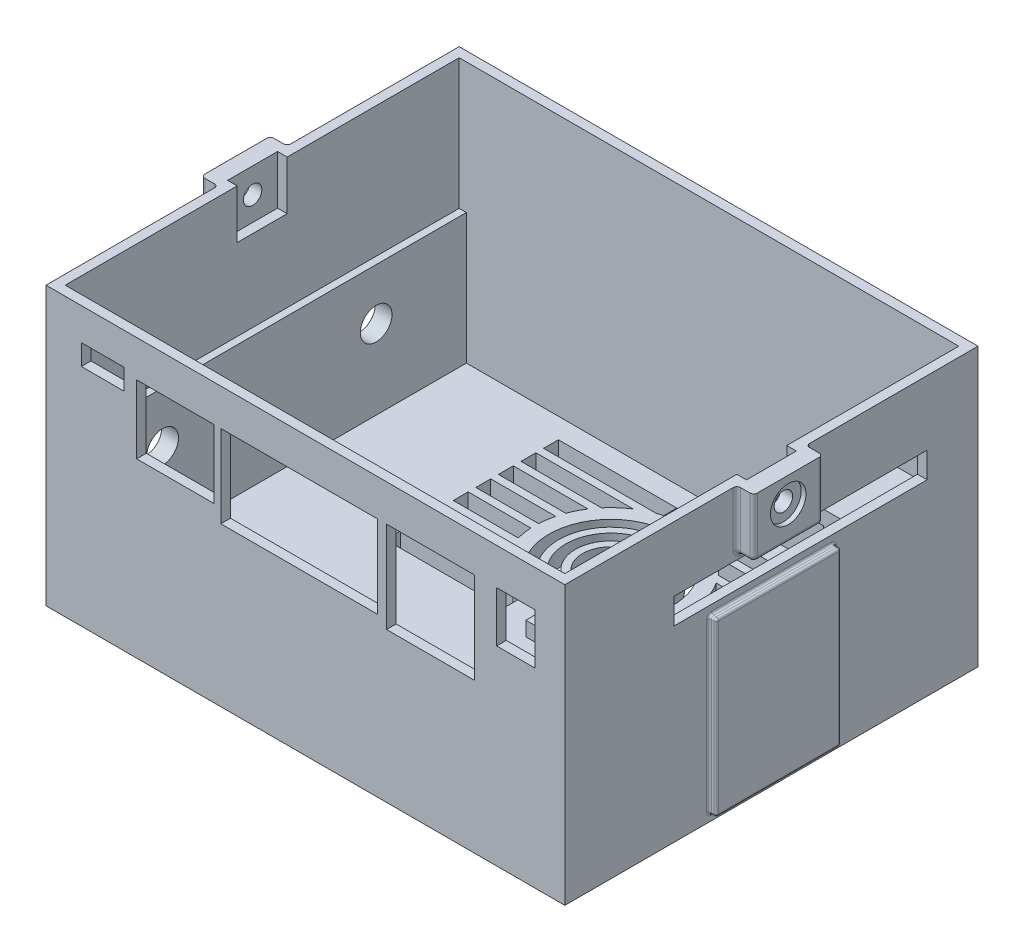
SolidWorks part; units mm, degrees
material "Custom Plastic"
ref_plane "Front Plane" through (0, 0, 0) normal (0, 0, 1) x (1, 0, 0)
ref_plane "Top Plane" through (0, 0, 0) normal (0, 1, 0) x (1, 0, 0)
ref_plane "Right Plane" through (0, 0, 0) normal (1, 0, 0) x (0, 0, -1)
sketch "Sketch1" plane through (0, 0, 0) normal (0, 1, 0) x (1, 0, 0)
  line L1 (54, -43) -> (-54, -43)
  line L2 (54, -43) -> (54, 43)
  line L3 (54, 43) -> (-54, 43)
  line L4 (-54, -43) -> (-54, 43)
  line L5 (54, -43) -> (-54, 43) construction
  line L6 (54, 43) -> (-54, -43) construction
  point P0 (0, 0)
  dimension "D1" = 108
  dimension "D2" = 86
extrude "Boss-Extrude1" add sketch "Sketch1" along normal blind 1.5
sketch "Sketch2" plane through (0, 1.5, 0) normal (0, 1, 0) x (1, 0, 0)
  line L4 (-54, 43) -> (-54, -43)
  line L5 (-54, -43) -> (54, -43)
  line L6 (54, -43) -> (54, 43)
  line L7 (54, 43) -> (-54, 43)
  line L8 (-54, 43) -> (-54, -43)
  line L9 (-54, -43) -> (54, -43)
  line L10 (54, -43) -> (54, 43)
  line L11 (54, 43) -> (-54, 43)
  dimension "D1" = 0
extrude "Boss-Extrude2" add sketch "Sketch2" along normal blind 56.3
shell "Shell1" thickness 2
sketch "Sketch3" plane through (54, 0, 0) normal (1, 0, 0) x (0, 0, -1)
  line L0 (0, -5.9802) -> (0, 60.3396) construction
  line L1 (-43, 57.8) -> (43, 57.8) construction
  line L2 (5.2, 47.5875) -> (-5.2, 47.5875)
  line L3 (5.2, 47.5875) -> (5.2, 57.8)
  line L4 (5.2, 57.8) -> (-5.2, 57.8)
  line L5 (-5.2, 47.5875) -> (-5.2, 57.8)
  line L6 (5.2, 47.5875) -> (-5.2, 57.8) construction
  line L7 (5.2, 57.8) -> (-5.2, 47.5875) construction
  point P3 (0, 52.6937)
  dimension "D1" = 10.2125
  dimension "D2" = 10.4
extrude "Cut-Extrude1" cut sketch "Sketch3" against normal through all
sketch "Sketch4" plane through (54, 0, 0) normal (1, 0, 0) x (0, 0, -1)
  line L0 (-7.2, 57.8) -> (-7.2, 45.5875)
  line L1 (-43, 57.8) -> (-5.2, 57.8) construction
  line L2 (-7.2, 45.5875) -> (7.2, 45.5875)
  line L3 (7.2, 45.5875) -> (7.2, 57.8)
  line L4 (5.2, 57.8) -> (43, 57.8) construction
  line L5 (7.2, 57.8) -> (-7.2, 57.8)
  line L6 (-5.2, 57.8) -> (-5.2, 47.5875) construction
  line L7 (5.2, 47.5875) -> (5.2, 57.8) construction
  line L8 (-5.2, 47.5875) -> (5.2, 47.5875) construction
  dimension "D1" = 2
  dimension "D2" = 2
  dimension "D3" = 2
extrude "Boss-Extrude3" add sketch "Sketch4" along normal blind 3.5
ref_plane "Plane1" through (0, 0, 0) normal (1, 0, 0) x (0, 0, -1)
mirror "Mirror1" about plane through (0, 0, 0) normal (1, 0, 0) of "Boss-Extrude3"
sketch "Sketch5" plane through (57.5, 0, 0) normal (1, 0, 0) x (0, 0, -1)
  line L0 (-7.2, 45.5875) -> (7.2, 45.5875) construction
  circle A0 centre (0, 52.5875) radius 1.925
  point P4 (0, 45.5875)
  dimension "D1" = 3.85
  dimension "D2" = 7
extrude "Cut-Extrude2" cut sketch "Sketch5" against normal through all
fillet "Fillet1" radius 0.75 1 edges at (57.5, 51.6937, 7.2)
fillet "Fillet2" radius 0.75 3 edges at (55.375, 45.5875, 7.2) (57.5, 45.5875, -0.375) (57.2803, 45.5875, 6.9803)
fillet "Fillet3" radius 0.75 3 edges at (55.375, 45.5875, -7.2) (57.5, 52.0687, -7.2) (57.2803, 45.8072, -7.2)
fillet "Fillet4" radius 0.75 5 edges at (54, 45.5875, 0) (54, 45.8072, 6.9803) (54, 52.0687, -7.2) (54, 45.8072, -6.9803) (54, 52.0687, 7.2)
fillet "Fillet5" radius 0.75 1 edges at (-57.5, 51.6937, -7.2)
fillet "Fillet6" radius 0.75 3 edges at (-55.375, 45.5875, -7.2) (-57.2803, 45.5875, -6.9803) (-57.5, 45.5875, 0.375)
fillet "Fillet7" radius 0.75 3 edges at (-55.375, 45.5875, 7.2) (-57.2803, 45.8072, 7.2) (-57.5, 52.0687, 7.2)
fillet "Fillet8" radius 0.75 5 edges at (-54, 52.0687, -7.2) (-54, 45.8072, -6.9803) (-54, 45.5875, 0) (-54, 45.8072, 6.9803) (-54, 52.0687, 7.2)
sketch "Sketch6" plane through (52, 0, 0) normal (-1, 0, 0) x (0, 0, 1)
  line L0 (-43, 0) -> (43, 0) construction
  line L1 (11, 35.26) -> (-11, 35.26)
  line L2 (11, 35.26) -> (11, 3.5)
  line L3 (11, 3.5) -> (-11, 3.5)
  line L4 (-11, 35.26) -> (-11, 3.5)
  line L5 (11, 35.26) -> (-11, 3.5) construction
  line L6 (11, 3.5) -> (-11, 35.26) construction
  line L7 (-43, 57.8) -> (-43, 0) construction
  point P0 (0, 19.38)
  point P7 (0, 3.5)
  dimension "D1" = 3.5
  dimension "D2" = 22
  dimension "D3" = 31.76
  dimension "D4" = 32
extrude "Cut-Extrude3" cut sketch "Sketch6" against normal blind 1.5
sketch "Sketch7" plane through (54, 0, 0) normal (1, 0, 0) x (0, 0, -1)
  line L1 (13, 1.5) -> (13, 37.26)
  line L2 (13, 37.26) -> (-13, 37.26)
  line L3 (-13, 37.26) -> (-13, 1.5)
  line L12 (-13, 1.5) -> (13, 1.5)
  line L13 (-43, 0) -> (43, 0) construction
  line L14 (43, 57.8) -> (43, 0) construction
  dimension "D1" = 1.5
  dimension "D2" = 26
  dimension "D3" = 35.76
  dimension "D4" = 30
extrude "Boss-Extrude4" add sketch "Sketch7" along normal blind 1.5
fillet "Fillet9" radius 0.5 1 edges at (55.5, 19.38, 13)
fillet "Fillet10" radius 0.5 3 edges at (54.5, 1.5, 13) (55.5, 1.5, -0.25) (55.3536, 1.5, 12.8536)
fillet "Fillet11" radius 0.5 3 edges at (54.5, 1.5, -13) (55.5, 19.63, -13) (55.3536, 1.6464, -13)
fillet "Fillet12" radius 0.5 5 edges at (54.5, 37.26, 13) (55.3536, 37.26, 12.8536) (54.5, 37.26, -13) (55.5, 37.26, 0) (55.3536, 37.26, -12.8536)
fillet "Fillet13" radius 0.5 8 edges at (54, 1.5, 0) (54, 1.6464, 12.8536) (54, 19.38, -13) (54, 1.6464, -12.8536) (54, 37.26, 0) (54, 19.38, 13) (54, 37.1136, 12.8536) (54, 37.1136, -12.8536)
sketch "Sketch8" plane through (-54, 0, 0) normal (-1, 0, 0) x (0, 0, 1)
  line L0 (-43, 0) -> (43, 0) construction
  circle A0 centre (-22.225, 20) radius 3.3
  circle A1 centre (22.225, 20) radius 3.3
  dimension "D1" = 6.6
  dimension "D2" = 6.6
  dimension "D3" = 44.45
  dimension "D4" = 20
  dimension "D5" = 22.225
extrude "Cut-Extrude4" cut sketch "Sketch8" against normal up to next
sketch "Sketch9" plane through (0, 3.5, 0) normal (0, 1, 0) x (1, 0, 0)
  arc A1 (40.2499, 0) -> (45.7499, 0) centre (42.9999, 0) ccw construction
  circle A2 centre (42.9999, 0) radius 7.7
  dimension "D1" = 15.4
extrude "Cut-Extrude5" cut sketch "Sketch9" against normal blind 1.5
sketch "Sketch10" plane through (0, 0, 0) normal (0, -1, 0) x (1, 0, 0)
  arc A0 (33.9999, 8) -> (35.9999, 8) centre (34.9999, 8) ccw construction
  arc A1 (49.9999, 8) -> (51.9999, 8) centre (50.9999, 8) ccw construction
  arc A2 (49.9999, -8) -> (51.9999, -8) centre (50.9999, -8) ccw construction
  arc A3 (33.9999, -8) -> (35.9999, -8) centre (34.9999, -8) ccw construction
  circle A8 centre (34.9999, -8) radius 1
  circle A9 centre (34.9999, 8) radius 1
  circle A10 centre (50.9999, 8) radius 1
  circle A11 centre (50.9999, -8) radius 1
extrude "Cut-Extrude7" cut sketch "Sketch10" against normal up to surface (3.5 mm away) up to face at (42.9999, 3.5, 7.7)
chamfer "Chamfer1" distance 1.2 angle 45 4 edges at (34.9999, 0, 7) (50.9999, 0, 7) (34.9999, 0, -9) (50.9999, 0, -9)
sketch "Sketch14" plane through (54, 0, 0) normal (1, 0, 0) x (0, 0, -1)
  line L20 (-20.2401, 44.3579) -> (32.4271, 44.3579)
  line L21 (-20.2401, 44.3579) -> (-20.2401, 39.0057)
  line L22 (-20.2401, 39.0057) -> (32.4271, 39.0057)
  line L23 (32.4271, 44.3579) -> (32.4271, 39.0057)
extrude "Cut-Extrude14" cut sketch "Sketch14" against normal up to next
sketch "Sketch15" plane through (57.5, 0, 0) normal (1, 0, 0) x (0, 0, -1)
  circle A2 centre (0, 52.5875) radius 3.7
  circle A3 centre (0, 52.5875) radius 3.5 construction
  dimension "D1" = 7.4
  dimension "D2" = 0.2
extrude "Cut-Extrude15" cut sketch "Sketch15" against normal blind 1
mirror "Mirror2" about plane through (0, 0, 0) normal (1, 0, 0) of "Cut-Extrude15"
sketch "Sketch16" plane through (52, 0, 0) normal (-1, 0, 0) x (0, 0, 1)
  line L1 (-33.1201, 34.46) -> (-33.1201, 37.46)
  line L5 (-33.1201, 37.46) -> (-17.8801, 37.46)
  line L6 (-17.8801, 37.46) -> (-17.8801, 34.46)
  line L7 (-33.1201, 13.8583) -> (-33.1201, 10.8583)
  line L8 (33.12, 13.8583) -> (17.88, 13.8583)
  line L9 (17.88, 34.46) -> (33.12, 34.46)
  line L10 (-17.8801, 13.8583) -> (-33.1201, 13.8583)
  line L11 (-33.1201, 34.46) -> (-17.8801, 34.46)
  line L12 (-33.1201, 10.8583) -> (-17.8801, 10.8583)
  line L13 (-17.8801, 10.8583) -> (-17.8801, 13.8583)
  line L14 (17.88, 13.8583) -> (17.88, 10.8583)
  line L15 (17.88, 10.8583) -> (33.12, 10.8583)
  line L16 (33.12, 10.8583) -> (33.12, 13.8583)
  line L17 (17.88, 34.46) -> (17.88, 37.46)
  line L18 (17.88, 37.46) -> (33.12, 37.46)
  line L19 (33.12, 37.46) -> (33.12, 34.46)
  line L20 (-43, 0) -> (43, 0) construction
  line L21 (-43, 57.8) -> (-43, 0) construction
  dimension "D1" = 3
  dimension "D2" = 3
  dimension "D3" = 3
  dimension "D4" = 3
  dimension "D5" = 15.24
  dimension "D6" = 15.24
  dimension "D7" = 15.24
  dimension "D8" = 15.24
  dimension "D9" = 10.8583
  dimension "D10" = 9.8799
  dimension "D11" = 35.7601
  dimension "D12" = 35.7601
  dimension "D13" = 9.8799
  dimension "D14" = 20.6017
extrude "Boss-Extrude5" add sketch "Sketch16" along normal blind 16
sketch "Sketch17" plane through (0, 13.8583, 0) normal (0, 1, 0) x (1, 0, 0)
  line L0 (47, 17.8801) -> (47, 33.1201)
  line L1 (47, -33.12) -> (47, -17.88)
  line L4 (52, 17.8801) -> (52, 33.1201)
  line L5 (52, 33.1201) -> (36, 33.1201)
  line L6 (36, 33.1201) -> (36, 17.8801)
  line L7 (36, 17.8801) -> (52, 17.8801)
  line L8 (52, 17.8801) -> (52, 33.1201)
  line L9 (52, 33.1201) -> (47, 33.1201)
  line L11 (47, 17.8801) -> (52, 17.8801)
  line L13 (52, -33.12) -> (52, -17.88)
  line L14 (52, -17.88) -> (36, -17.88)
  line L15 (36, -17.88) -> (36, -33.12)
  line L16 (36, -33.12) -> (52, -33.12)
  line L17 (52, -33.12) -> (52, -17.88)
  line L18 (52, -17.88) -> (47, -17.88)
  line L20 (47, -33.12) -> (52, -33.12)
  dimension "D3" = 5
  dimension "D4" = 5
  dimension "D1" = 0
  dimension "D2" = 0
extrude "Boss-Extrude6" add sketch "Sketch17" along normal blind 5
ref_plane "Plane2" through (0, 24.1592, 0) normal (0, 1, 0) x (1, 0, 0)
mirror "Mirror3" about plane through (0, 24.1592, 0) normal (0, 1, 0) of "Boss-Extrude6"
sketch "Sketch19" plane through (-52, 0, 0) normal (1, 0, 0) x (0, 0, -1)
  line L0 (41, 57.8) -> (41, 3.5) construction
  line L1 (-41, 57.8) -> (-41, 3.5) construction
  line L2 (41, 3.5) -> (-41, 3.5) construction
  line L3 (41, 30.65) -> (41, 3.5)
  line L4 (-41, 30.65) -> (-41, 3.5)
  line L5 (41, 3.5) -> (-41, 3.5)
  line L6 (-41, 30.65) -> (41, 30.65)
  dimension "D1" = 27.15
extrude "Boss-Extrude7" add sketch "Sketch19" along normal blind 1.5
sketch "Sketch20" plane through (0, 13.8583, 0) normal (0, 1, 0) x (1, 0, 0)
  line L0 (41.5, -33.12) -> (41.5, -17.88)
  line L1 (41.5, 17.8801) -> (41.5, 33.1201)
  line L4 (47, -33.12) -> (47, -17.88)
  line L5 (47, -17.88) -> (36, -17.88)
  line L6 (36, -17.88) -> (36, -33.12)
  line L7 (36, -33.12) -> (47, -33.12)
  line L9 (41.5, -17.88) -> (36, -17.88)
  line L10 (36, -17.88) -> (36, -33.12)
  line L11 (36, -33.12) -> (41.5, -33.12)
  line L13 (47, 17.8801) -> (47, 33.1201)
  line L14 (47, 33.1201) -> (36, 33.1201)
  line L15 (36, 33.1201) -> (36, 17.8801)
  line L16 (36, 17.8801) -> (47, 17.8801)
  line L18 (41.5, 33.1201) -> (36, 33.1201)
  line L19 (36, 33.1201) -> (36, 17.8801)
  line L20 (36, 17.8801) -> (41.5, 17.8801)
  dimension "D2" = 5.5
  dimension "D4" = 5.5
  dimension "D1" = 0
  dimension "D3" = 0
extrude "Cut-Extrude16" cut sketch "Sketch20" against normal up to next
chamfer "Chamfer2" distance 1 angle 45 2 edges at (41.5, 13.8583, -25.5001) (41.5, 13.8583, 25.5)
sketch "Sketch21" plane through (0, 34.46, 0) normal (0, -1, 0) x (1, 0, 0)
  line L20 (42.5, 21.8023) -> (42.5, 29.3023)
  line L21 (42.5, -29.3001) -> (42.5, -21.8001)
  line L23 (42.5, 21.8023) -> (40, 21.8023)
  line L24 (40, 21.8023) -> (40, 29.3023)
  line L25 (42.5, 29.3023) -> (40, 29.3023)
  line L26 (36, 17.88) -> (36, 33.12) construction
  line L27 (36, 33.12) -> (47, 33.12) construction
  line L28 (36, 17.88) -> (47, 17.88) construction
  line L29 (42.5, -21.8001) -> (40, -21.8001)
  line L30 (40, -21.8001) -> (40, -29.3001)
  line L31 (40, -29.3001) -> (42.5, -29.3001)
  line L32 (36, -33.1201) -> (52, -33.1201) construction
  point P3 (41.25, 29.3023)
  dimension "D3" = 2.5
  dimension "D4" = 7.5
  dimension "D1" = 4
  dimension "D5" = 3.8177
  dimension "D6" = 3.9223
  dimension "D2" = 7.5
  dimension "D7" = 3.82
extrude "Boss-Extrude8" add sketch "Sketch21" along normal blind 2
chamfer "Chamfer3" distance 0.75 angle 45 2 edges at (42.5, 32.46, -25.5501) (42.5, 32.46, 25.5523)
sketch "Sketch22" plane through (0, 0, 43) normal (0, 0, 1) x (1, 0, 0)
  line L1 (47.8, 39.6675) -> (47.8, 49.6675) construction
  line L2 (39.8, 49.6675) -> (39.8, 39.6675) construction
  line L3 (39.8, 39.6675) -> (47.8, 39.6675) construction
  line L5 (47.8, 39.6675) -> (47.8, 50.1675)
  line L6 (39.8, 50.1675) -> (39.8, 39.6675)
  line L7 (39.8, 39.6675) -> (47.8, 39.6675)
  line L8 (49.2, 50.1675) -> (-49.6, 50.1675) construction
  line L9 (47.8, 50.1675) -> (39.8, 50.1675)
  line L41 (-46.6551, 51.1264) -> (-37.7598, 51.1264)
  line L42 (-46.6551, 51.1264) -> (-46.6551, 46.8159)
  line L43 (-46.6551, 46.8159) -> (-37.7598, 46.8159)
  line L44 (-37.7598, 51.1264) -> (-37.7598, 46.8159)
  line L45 (-35.1344, 50.1675) -> (-19.0694, 50.1675)
  line L46 (-35.1344, 50.1675) -> (-35.1344, 35.9249)
  line L47 (-35.1344, 35.9249) -> (-19.0694, 35.9249)
  line L48 (-19.0694, 50.1675) -> (-19.0694, 35.9249)
  line L49 (-17.6118, 50.1675) -> (14.9908, 50.1675)
  line L50 (-17.6118, 50.1675) -> (-17.6118, 32.9825)
  line L51 (-17.6118, 32.9825) -> (14.9908, 32.9825)
  line L52 (14.9908, 50.1675) -> (14.9908, 32.9825)
  line L53 (16.8847, 50.1675) -> (35.2203, 50.1675)
  line L54 (16.8847, 50.1675) -> (16.8847, 31.1706)
  line L55 (16.8847, 31.1706) -> (35.2203, 31.1706)
  line L56 (35.2203, 50.1675) -> (35.2203, 31.1706)
extrude "Cut-Extrude17" cut sketch "Sketch22" against normal up to next
sketch "Sketch23" plane through (0, 0, 0) normal (0, -1, 0) x (1, 0, 0)
  line L0 (19.4635, -13.275) -> (16.6823, -13.275)
  line L1 (19.8842, -14.875) -> (17.1793, -14.875)
  line L2 (19.8842, -22.675) -> (17.1793, -22.675)
  line L3 (19.4635, -24.275) -> (16.6823, -24.275)
  line L12 (-15.8635, -13.275) -> (-13.0823, -13.275)
  line L13 (-16.2842, -14.875) -> (-13.5793, -14.875)
  line L14 (-16.2842, -22.675) -> (-13.5793, -22.675)
  line L15 (-15.8635, -24.275) -> (-13.0823, -24.275)
  line L16 (1, -14.9824) -> (1, -12.9537)
  line L18 (1, -31.6261) -> (1, -29.6215)
  line L20 (2.6, -31.6261) -> (2.6, -29.6215)
  line L22 (6.072, -0.775) -> (6.072, -3.4949)
  line L23 (-2.472, -36.775) -> (-2.472, -34.0551)
  line L24 (6.072, -34.0551) -> (6.072, -36.775)
  line L30 (-2.472, -3.4949) -> (-2.472, -0.775)
  line L41 (2.6, -14.9824) -> (2.6, -12.9537)
  line L43 (1, -7.9285) -> (1, -5.9239)
  line L45 (1, -11.4425) -> (1, -9.4332)
  line L46 (1, -28.1168) -> (1, -26.1075)
  line L47 (1, -24.5963) -> (1, -22.5676)
  line L48 (2.6, -7.9285) -> (2.6, -5.9239)
  line L49 (2.6, -11.4425) -> (2.6, -9.4332)
  line L50 (2.6, -24.5963) -> (2.6, -22.5676)
  line L51 (2.6, -28.1168) -> (2.6, -26.1075)
  line L56 (-15.8635, -24.275) -> (-27.1, -24.275)
  line L57 (-27.1, -24.275) -> (-27.1, -27.375)
  line L58 (-27.1, -27.375) -> (-14.5796, -27.375)
  line L59 (-13.6341, -28.975) -> (-27.1, -28.975)
  line L60 (-27.1, -28.975) -> (-27.1, -32.075)
  line L61 (-27.1, -32.075) -> (-11.0592, -32.075)
  line L62 (-9.1654, -33.675) -> (-27.1, -33.675)
  line L63 (-27.1, -33.675) -> (-27.1, -36.775)
  line L64 (-27.1, -36.775) -> (-2.472, -36.775)
  line L65 (6.072, -36.775) -> (30.7, -36.775)
  line L66 (30.7, -36.775) -> (30.7, -33.675)
  line L67 (30.7, -33.675) -> (12.7654, -33.675)
  line L68 (14.6592, -32.075) -> (30.7, -32.075)
  line L69 (30.7, -32.075) -> (30.7, -28.975)
  line L70 (30.7, -28.975) -> (17.2341, -28.975)
  line L71 (18.1796, -27.375) -> (30.7, -27.375)
  line L72 (30.7, -27.375) -> (30.7, -24.275)
  line L73 (30.7, -24.275) -> (19.4635, -24.275)
  line L74 (19.8842, -22.675) -> (30.7, -22.675)
  line L75 (30.7, -22.675) -> (30.7, -19.575)
  line L76 (30.7, -19.575) -> (20.2827, -19.575)
  line L77 (20.2827, -17.975) -> (30.7, -17.975)
  line L78 (30.7, -17.975) -> (30.7, -14.875)
  line L79 (30.7, -14.875) -> (19.8842, -14.875)
  line L80 (19.4635, -13.275) -> (30.7, -13.275)
  line L81 (30.7, -13.275) -> (30.7, -10.175)
  line L82 (30.7, -10.175) -> (18.1796, -10.175)
  line L83 (17.2341, -8.575) -> (30.7, -8.575)
  line L84 (30.7, -8.575) -> (30.7, -5.475)
  line L85 (30.7, -5.475) -> (14.6592, -5.475)
  line L86 (12.7654, -3.875) -> (30.7, -3.875)
  line L87 (30.7, -3.875) -> (30.7, -0.775)
  line L88 (30.7, -0.775) -> (6.072, -0.775)
  line L89 (-2.472, -0.775) -> (-27.1, -0.775)
  line L90 (-27.1, -0.775) -> (-27.1, -3.875)
  line L91 (-27.1, -3.875) -> (-9.1654, -3.875)
  line L92 (-11.0592, -5.475) -> (-27.1, -5.475)
  line L93 (-27.1, -5.475) -> (-27.1, -8.575)
  line L94 (-27.1, -8.575) -> (-13.6341, -8.575)
  line L95 (-14.5796, -10.175) -> (-27.1, -10.175)
  line L96 (-27.1, -10.175) -> (-27.1, -13.275)
  line L97 (-27.1, -13.275) -> (-15.8635, -13.275)
  line L98 (-16.2842, -14.875) -> (-27.1, -14.875)
  line L99 (-27.1, -14.875) -> (-27.1, -17.975)
  line L100 (-27.1, -17.975) -> (-16.6827, -17.975)
  line L101 (-16.6827, -19.575) -> (-27.1, -19.575)
  line L102 (-27.1, -19.575) -> (-27.1, -22.675)
  line L103 (-27.1, -22.675) -> (-16.2842, -22.675)
  line L104 (-15.8635, -24.275) -> (-27.1, -24.275)
  line L105 (-27.1, -24.275) -> (-27.1, -27.375)
  line L106 (-27.1, -27.375) -> (-11.5331, -27.375)
  line L107 (-10.3528, -28.975) -> (-27.1, -28.975)
  line L108 (-27.1, -28.975) -> (-27.1, -32.075)
  line L109 (-27.1, -32.075) -> (-6.8511, -32.075)
  line L110 (-3.6518, -33.675) -> (-27.1, -33.675)
  line L111 (-27.1, -33.675) -> (-27.1, -36.775)
  line L112 (-27.1, -36.775) -> (-2.472, -36.775)
  line L113 (6.072, -36.775) -> (30.7, -36.775)
  line L114 (30.7, -36.775) -> (30.7, -33.675)
  line L115 (30.7, -33.675) -> (7.2518, -33.675)
  line L116 (10.4511, -32.075) -> (30.7, -32.075)
  line L117 (30.7, -32.075) -> (30.7, -28.975)
  line L118 (30.7, -28.975) -> (13.9528, -28.975)
  line L119 (15.1331, -27.375) -> (30.7, -27.375)
  line L120 (30.7, -27.375) -> (30.7, -24.275)
  line L121 (30.7, -24.275) -> (19.4635, -24.275)
  line L122 (19.8842, -22.675) -> (30.7, -22.675)
  line L123 (30.7, -22.675) -> (30.7, -19.575)
  line L124 (30.7, -19.575) -> (17.6459, -19.575)
  line L125 (17.6459, -17.975) -> (30.7, -17.975)
  line L126 (30.7, -17.975) -> (30.7, -14.875)
  line L127 (30.7, -14.875) -> (19.8842, -14.875)
  line L128 (19.4635, -13.275) -> (30.7, -13.275)
  line L129 (30.7, -13.275) -> (30.7, -10.175)
  line L130 (30.7, -10.175) -> (15.1331, -10.175)
  line L131 (13.9528, -8.575) -> (30.7, -8.575)
  line L132 (30.7, -8.575) -> (30.7, -5.475)
  line L133 (30.7, -5.475) -> (10.4511, -5.475)
  line L134 (7.2518, -3.875) -> (30.7, -3.875)
  line L135 (30.7, -3.875) -> (30.7, -0.775)
  line L136 (30.7, -0.775) -> (6.072, -0.775)
  line L137 (-2.472, -0.775) -> (-27.1, -0.775)
  line L138 (-27.1, -0.775) -> (-27.1, -3.875)
  line L139 (-27.1, -3.875) -> (-3.6518, -3.875)
  line L140 (-6.8511, -5.475) -> (-27.1, -5.475)
  line L141 (-27.1, -5.475) -> (-27.1, -8.575)
  line L142 (-27.1, -8.575) -> (-10.3528, -8.575)
  line L143 (-11.5331, -10.175) -> (-27.1, -10.175)
  line L144 (-27.1, -10.175) -> (-27.1, -13.275)
  line L145 (-27.1, -13.275) -> (-15.8635, -13.275)
  line L146 (-16.2842, -14.875) -> (-27.1, -14.875)
  line L147 (-27.1, -14.875) -> (-27.1, -17.975)
  line L148 (-27.1, -17.975) -> (-14.0459, -17.975)
  line L149 (-14.0459, -19.575) -> (-27.1, -19.575)
  line L150 (-27.1, -19.575) -> (-27.1, -22.675)
  line L151 (-27.1, -22.675) -> (-16.2842, -22.675)
  arc A0 (-2.472, -3.4949) -> (-3.6518, -3.875) centre (1.8, -18.775) ccw
  arc A1 (6.072, -6.6283) -> (2.6, -5.9239) centre (1.8, -18.775) ccw
  arc A5 (16.6823, -13.275) -> (15.1331, -10.175) centre (1.8, -18.775) ccw
  arc A8 (-2.472, -30.9217) -> (1, -31.6261) centre (1.8, -18.775) ccw
  arc A9 (6.072, -34.0551) -> (7.2518, -33.675) centre (1.8, -18.775) ccw
  arc A10 (17.1793, -22.675) -> (17.6459, -19.575) centre (1.8, -18.775) ccw
  arc A11 (-13.0823, -24.275) -> (-11.5331, -27.375) centre (1.8, -18.775) ccw
  arc A12 (-13.5793, -14.875) -> (-14.0459, -17.975) centre (1.8, -18.775) ccw
  arc A13 (-3.6518, -33.675) -> (-2.472, -34.0551) centre (1.8, -18.775) ccw
  arc A14 (-10.3528, -28.975) -> (-6.8511, -32.075) centre (1.8, -18.775) ccw
  arc A15 (-14.0459, -19.575) -> (-13.5793, -22.675) centre (1.8, -18.775) ccw
  arc A16 (-16.2842, -22.675) -> (-15.8635, -24.275) centre (1.8, -18.775) ccw
  arc A17 (-14.5796, -27.375) -> (-13.6341, -28.975) centre (1.8, -18.775) ccw
  arc A18 (-11.0592, -32.075) -> (-9.1654, -33.675) centre (1.8, -18.775) ccw
  arc A19 (-2.472, -36.775) -> (6.072, -36.775) centre (1.8, -18.775) ccw
  arc A20 (12.7654, -33.675) -> (14.6592, -32.075) centre (1.8, -18.775) ccw
  arc A21 (17.2341, -28.975) -> (18.1796, -27.375) centre (1.8, -18.775) ccw
  arc A22 (19.4635, -24.275) -> (19.8842, -22.675) centre (1.8, -18.775) ccw
  arc A23 (20.2827, -19.575) -> (20.2827, -17.975) centre (1.8, -18.775) ccw
  arc A24 (19.8842, -14.875) -> (19.4635, -13.275) centre (1.8, -18.775) ccw
  arc A25 (18.1796, -10.175) -> (17.2341, -8.575) centre (1.8, -18.775) ccw
  arc A26 (14.6592, -5.475) -> (12.7654, -3.875) centre (1.8, -18.775) ccw
  arc A27 (6.072, -0.775) -> (-2.472, -0.775) centre (1.8, -18.775) ccw
  arc A28 (-9.1654, -3.875) -> (-11.0592, -5.475) centre (1.8, -18.775) ccw
  arc A29 (-13.6341, -8.575) -> (-14.5796, -10.175) centre (1.8, -18.775) ccw
  arc A30 (-15.8635, -13.275) -> (-16.2842, -14.875) centre (1.8, -18.775) ccw
  arc A31 (-16.6827, -17.975) -> (-16.6827, -19.575) centre (1.8, -18.775) ccw
  arc A48 (-11.5331, -10.175) -> (-13.0823, -13.275) centre (1.8, -18.775) ccw
  arc A49 (-6.8511, -5.475) -> (-10.3528, -8.575) centre (1.8, -18.775) ccw
  arc A50 (10.4511, -32.075) -> (13.9528, -28.975) centre (1.8, -18.775) ccw
  arc A51 (15.1331, -27.375) -> (16.6823, -24.275) centre (1.8, -18.775) ccw
  arc A52 (17.6459, -17.975) -> (17.1793, -14.875) centre (1.8, -18.775) ccw
  arc A53 (13.9528, -8.575) -> (10.4511, -5.475) centre (1.8, -18.775) ccw
  arc A54 (7.2518, -3.875) -> (6.072, -3.4949) centre (1.8, -18.775) ccw
  arc A55 (2.6, -31.6261) -> (14.6511, -17.975) centre (1.8, -18.775) ccw
  arc A56 (1, -5.9239) -> (-11.0511, -19.575) centre (1.8, -18.775) ccw
  arc A57 (-11.0511, -19.575) -> (-2.472, -30.9217) centre (1.8, -18.775) ccw
  arc A58 (14.6511, -17.975) -> (6.072, -6.6283) centre (1.8, -18.775) ccw
  arc A59 (2.6, -29.6215) -> (2.6, -7.9285) centre (1.8, -18.775) ccw
  arc A60 (2.6, -28.1168) -> (2.6, -9.4332) centre (1.8, -18.775) ccw
  arc A61 (2.6, -26.1075) -> (2.6, -11.4425) centre (1.8, -18.775) ccw
  arc A62 (2.6, -24.5963) -> (2.6, -12.9537) centre (1.8, -18.775) ccw
  arc A63 (2.6, -22.5676) -> (2.6, -14.9824) centre (1.8, -18.775) ccw
  arc A64 (1, -5.9239) -> (-11.0511, -17.975) centre (1.8, -18.775) ccw construction
  arc A65 (1.1243, -7.92) -> (-9.055, -18.0993) centre (1.8, -18.775) ccw construction
  arc A66 (1.2175, -9.4171) -> (-7.5579, -18.1925) centre (1.8, -18.775) ccw construction
  arc A67 (1.3417, -11.4132) -> (-5.5618, -18.3167) centre (1.8, -18.775) ccw construction
  arc A68 (1.4349, -12.9103) -> (-4.0647, -18.4099) centre (1.8, -18.775) ccw construction
  arc A69 (1.5592, -14.9065) -> (-2.0685, -18.5342) centre (1.8, -18.775) ccw construction
  arc A70 (1, -14.9824) -> (1, -22.5676) centre (1.8, -18.775) ccw
  arc A71 (1, -12.9537) -> (1, -24.5963) centre (1.8, -18.775) ccw
  arc A72 (1, -11.4425) -> (1, -26.1075) centre (1.8, -18.775) ccw
  arc A73 (1, -9.4332) -> (1, -28.1168) centre (1.8, -18.775) ccw
  arc A74 (1, -7.9285) -> (1, -29.6215) centre (1.8, -18.775) ccw
  dimension "D4" = 0.8
  dimension "D5" = 0.8
  dimension "D2" = 0
  dimension "D6" = 2
  dimension "D7" = 1.5
  dimension "D8" = 2
  dimension "D9" = 1.5
  dimension "D10" = 2
extrude "Cut-Extrude18" cut sketch "Sketch23" against normal up to next
sketch "Sketch24" plane through (-52, 0, 0) normal (-1, 0, 0) x (0, 0, 1)
  circle A1 centre (22.225, 20) radius 3.3
  circle A2 centre (22.225, 20) radius 3.3
  circle A3 centre (-22.225, 20) radius 3.3
  circle A4 centre (-22.225, 20) radius 3.3
  dimension "D1" = 0
  dimension "D2" = 0
extrude "Cut-Extrude19" cut sketch "Sketch24" against normal up to next
